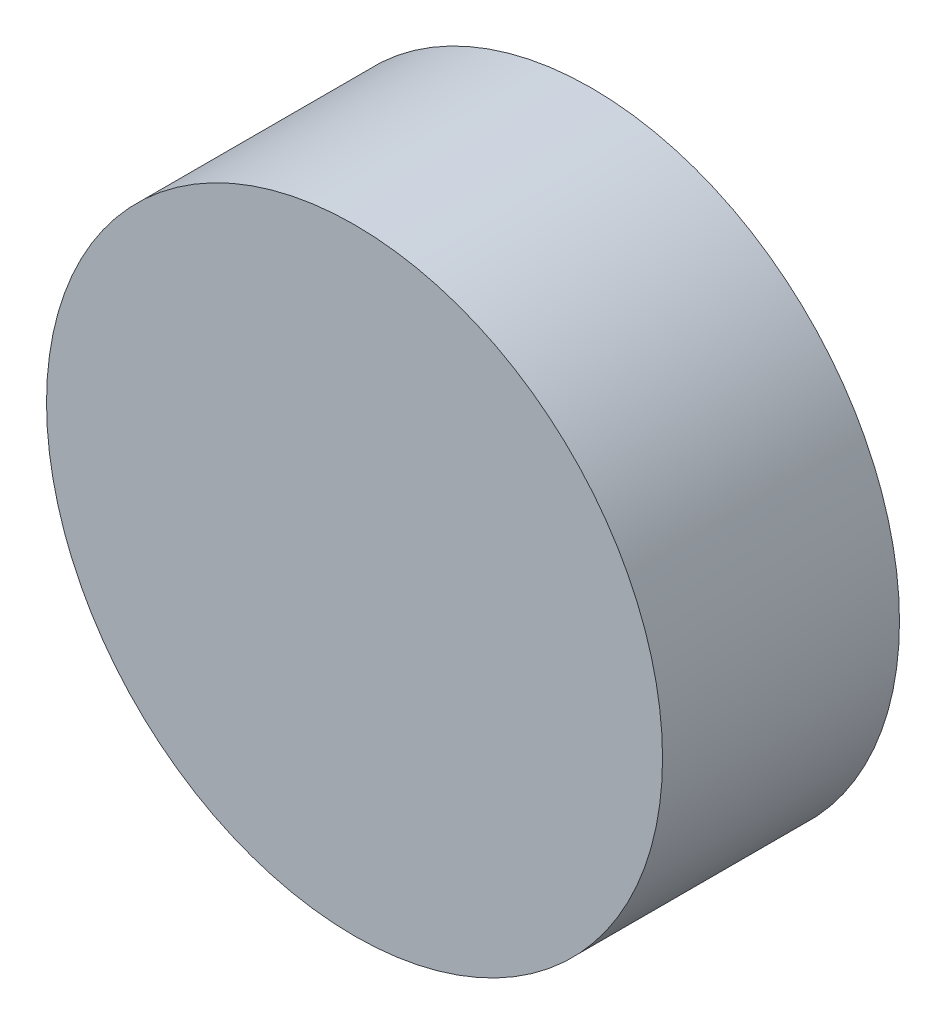
SolidWorks part; units mm, degrees
ref_plane "Front Plane" through (0, 0, 0) normal (0, 0, 1) x (1, 0, 0)
ref_plane "Top Plane" through (0, 0, 0) normal (0, 1, 0) x (1, 0, 0)
ref_plane "Right Plane" through (0, 0, 0) normal (1, 0, 0) x (0, 0, -1)
sketch "Sketch2" plane through (0, 0, 0) normal (0, 0, 1) x (1, 0, 0)
  circle A0 centre (0, 0) radius 32.5
  dimension "D1" = 65
extrude "Boss-Extrude1" add sketch "Sketch2" along normal blind 25 contours A0
sketch "Sketch3" plane through (0, 0, 0) normal (0, 0, -1) x (-1, 0, 0)
